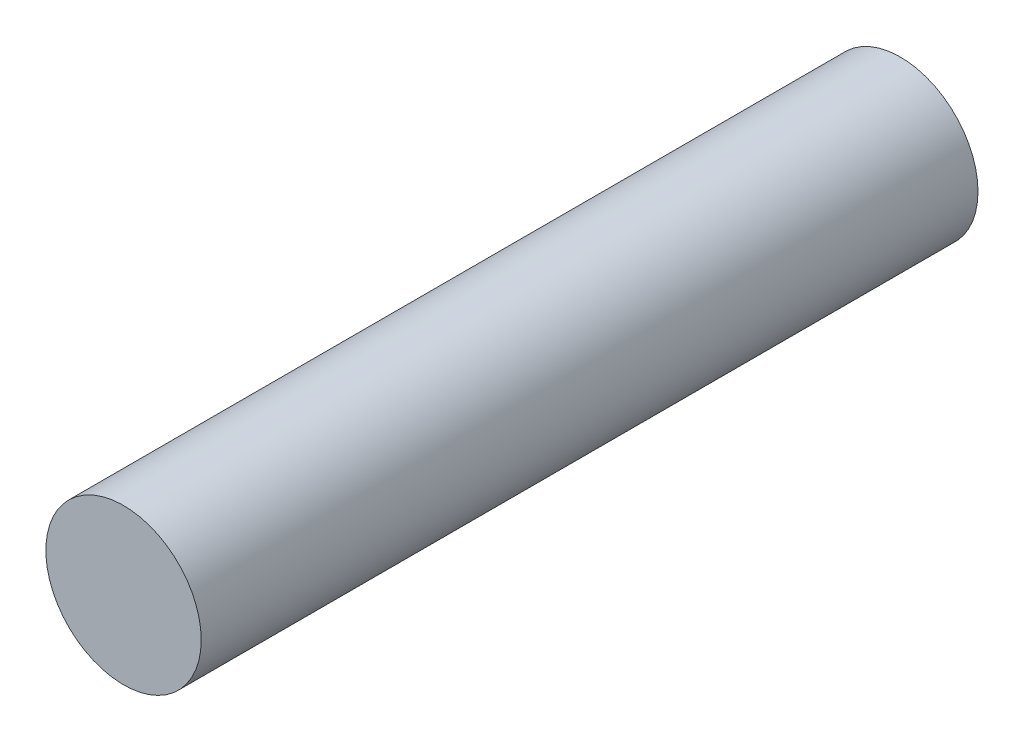
SolidWorks part; units mm, degrees
ref_plane "Alzado" through (0, 0, 0) normal (0, 0, 1) x (1, 0, 0)
ref_plane "Planta" through (0, 0, 0) normal (0, 1, 0) x (1, 0, 0)
ref_plane "Vista lateral" through (0, 0, 0) normal (1, 0, 0) x (0, 0, -1)
sketch "Croquis1" plane through (0, 0, 0) normal (0, 0, 1) x (1, 0, 0)
  circle A0 centre (-75.2387, 16.5365) radius 5
  point P2 (-183.2924, -30.0299)
extrude "Saliente-Extruir2" add sketch "Croquis1" along normal blind 50
